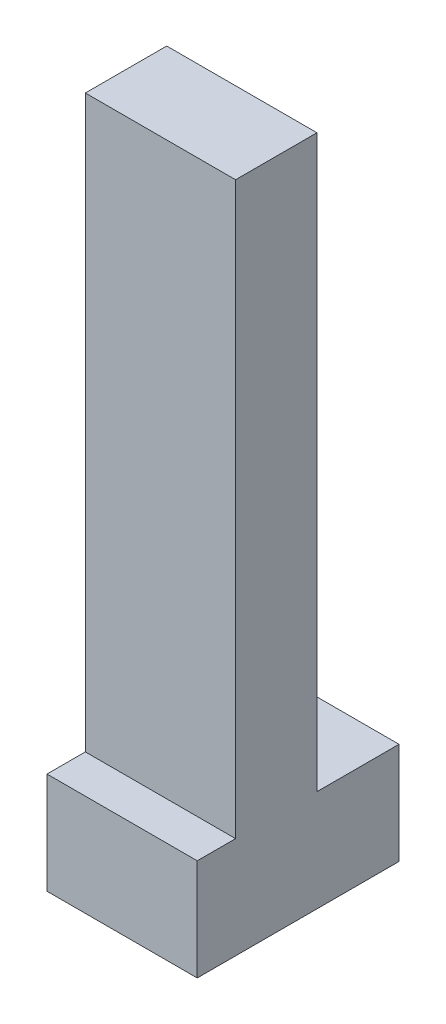
SolidWorks part; units mm, degrees
ref_plane "Front Plane" through (0, 0, 0) normal (0, 0, 1) x (1, 0, 0)
ref_plane "Top Plane" through (0, 0, 0) normal (0, 1, 0) x (1, 0, 0)
ref_plane "Right Plane" through (0, 0, 0) normal (1, 0, 0) x (0, 0, -1)
sketch "Sketch3" plane through (0, 0, 0) normal (1, 0, 0) x (0, 0, -1)
  line L0 (5.6389, 30.1169) -> (5.6389, -11.6623)
  line L1 (5.6389, -11.6623) -> (2.8319, -11.6623)
  line L2 (2.8319, -11.6623) -> (2.8319, -19.0954)
  line L3 (2.8319, -19.0954) -> (17.6041, -19.0954)
  line L4 (17.6041, -19.0954) -> (17.6041, -11.6623)
  line L5 (17.6041, -11.6623) -> (11.5967, -11.6623)
  line L6 (11.5967, -11.6623) -> (11.5967, 30.1169)
  line L7 (11.5967, 30.1169) -> (5.6389, 30.1169)
extrude "Boss-Extrude2" add sketch "Sketch3" along normal blind 11
